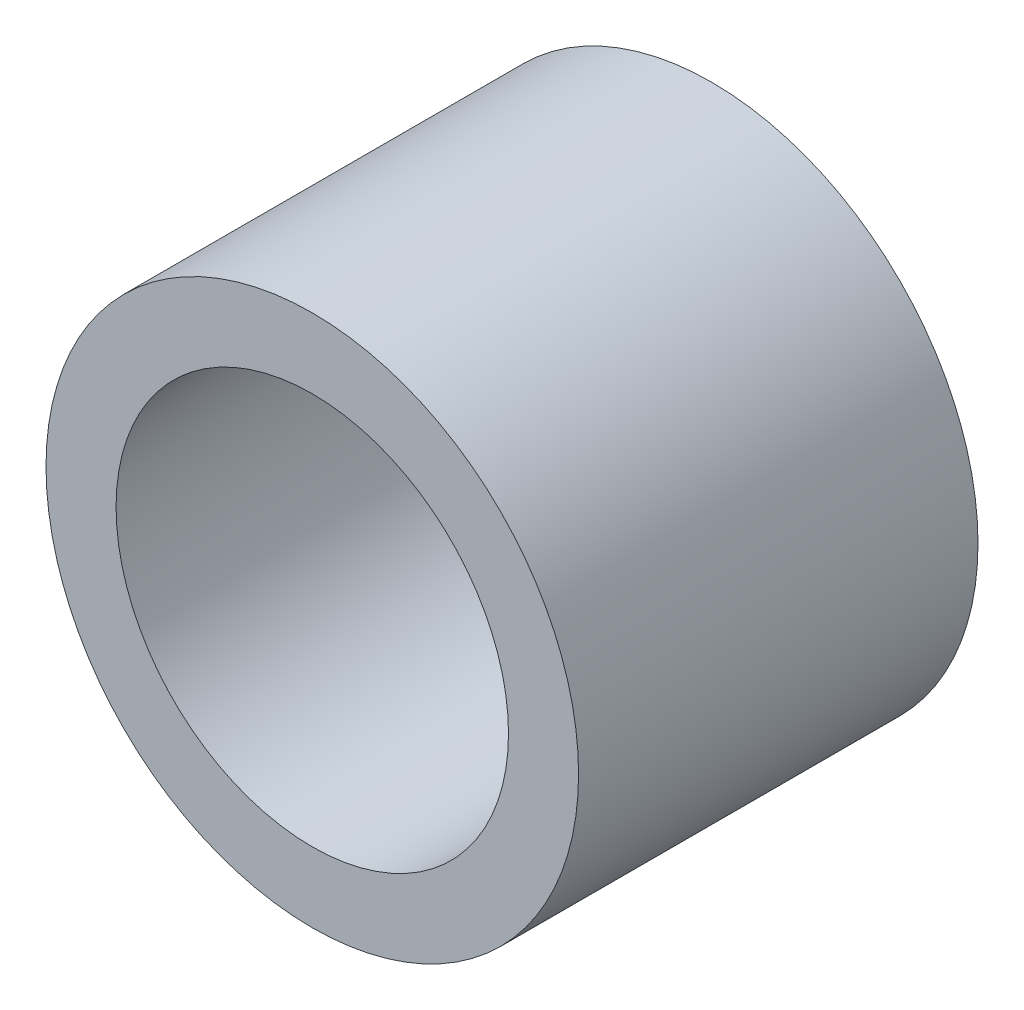
SolidWorks part; units mm, degrees
ref_plane "Front Plane" through (0, 0, 0) normal (0, 0, 1) x (1, 0, 0)
ref_plane "Top Plane" through (0, 0, 0) normal (0, 1, 0) x (1, 0, 0)
ref_plane "Right Plane" through (0, 0, 0) normal (1, 0, 0) x (0, 0, -1)
sketch "Sketch1" plane through (0, 0, 0) normal (0, 0, 1) x (1, 0, 0)
  circle A0 centre (0, 0) radius 2.8
  circle A1 centre (0, 0) radius 3.8
  dimension "D1" = 5.6
  dimension "D2" = 1
extrude "Boss-Extrude1" add sketch "Sketch1" along normal blind 5.7
